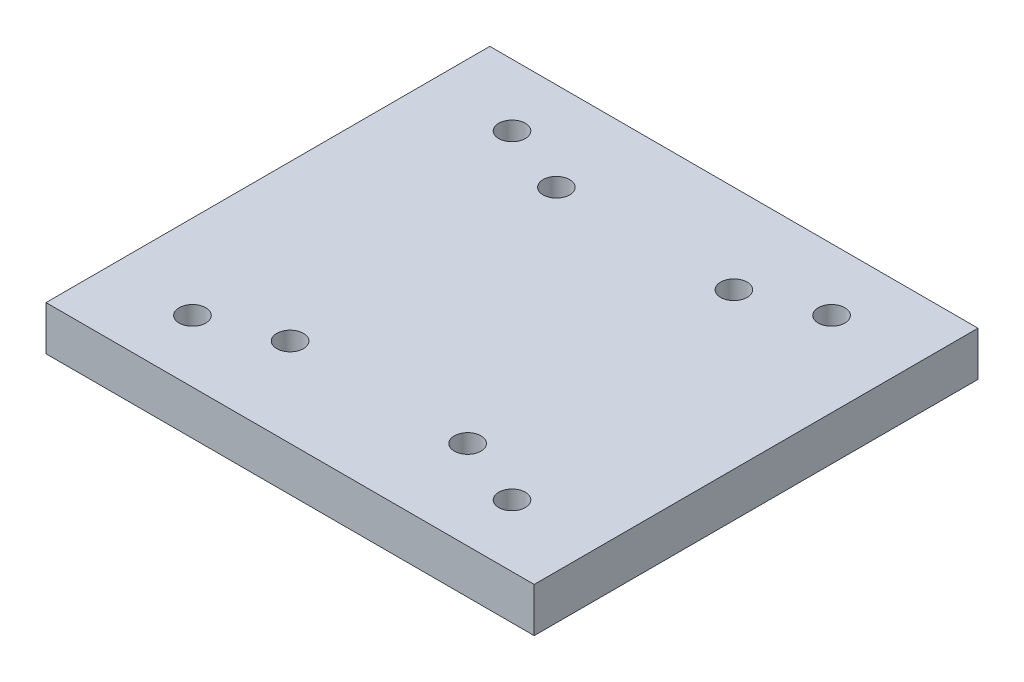
SolidWorks part; units mm, degrees
ref_plane "前视基准面" through (0, 0, 0) normal (0, 0, 1) x (1, 0, 0)
ref_plane "上视基准面" through (0, 0, 0) normal (0, 1, 0) x (1, 0, 0)
ref_plane "右视基准面" through (0, 0, 0) normal (1, 0, 0) x (0, 0, -1)
other "Configuration Table"
sketch "草图1" plane through (0, 0, 0) normal (0, 1, 0) x (1, 0, 0)
  line L1 (-27.5, 25) -> (27.5, 25)
  line L2 (-27.5, 25) -> (-27.5, -25)
  line L3 (-27.5, -25) -> (27.5, -25)
  line L4 (27.5, 25) -> (27.5, -25)
  line L5 (-27.5, 25) -> (27.5, -25) construction
  line L6 (-27.5, -25) -> (27.5, 25) construction
  point P0 (0, 0)
  dimension "D1" = 55
  dimension "D2" = 50
extrude "凸台-拉伸1" add sketch "草图1" along normal blind 5
sketch "草图2" plane through (0, 5, 0) normal (0, 1, 0) x (1, 0, 0)
  line L1 (-18, 18) -> (18, 18) construction
  line L2 (-18, 18) -> (-18, -18) construction
  line L3 (-18, -18) -> (18, -18) construction
  line L4 (18, 18) -> (18, -18) construction
  line L5 (-18, 18) -> (18, -18) construction
  line L6 (-18, -18) -> (18, 18) construction
  circle A0 centre (-18, 18) radius 1.5
  circle A1 centre (18, 18) radius 1.5
  circle A2 centre (18, -18) radius 1.5
  circle A3 centre (-18, -18) radius 1.5
  point P0 (0, 0)
  dimension "D3" = 3
  dimension "D1" = 36
  dimension "D2" = 36
extrude "切除-拉伸1" cut sketch "草图2" against normal through all
sketch "草图5" plane through (0, 5, 0) normal (0, 1, 0) x (1, 0, 0)
  line L1 (-10, 15) -> (10, 15) construction
  line L2 (-10, 15) -> (-10, -15) construction
  line L3 (-10, -15) -> (10, -15) construction
  line L4 (10, 15) -> (10, -15) construction
  line L5 (-10, 15) -> (10, -15) construction
  line L6 (-10, -15) -> (10, 15) construction
  circle A0 centre (-10, 15) radius 1.5
  circle A1 centre (10, 15) radius 1.5
  circle A2 centre (10, -15) radius 1.5
  circle A3 centre (-10, -15) radius 1.5
  point P0 (0, 0)
  dimension "D3" = 3
  dimension "D1" = 20
  dimension "D2" = 30
extrude "切除-拉伸2" cut sketch "草图5" against normal blind 10
sketch "草图3" plane through (0, 5, 0) normal (0, 1, 0) x (1, 0, 0)
  line L1 (-15.3442, 18) -> (-16.6721, 20.3)
  line L2 (-16.6721, 20.3) -> (-19.3279, 20.3)
  line L3 (-19.3279, 20.3) -> (-20.6558, 18)
  line L4 (-20.6558, 18) -> (-19.3279, 15.7)
  line L5 (-19.3279, 15.7) -> (-16.6721, 15.7)
  line L6 (-16.6721, 15.7) -> (-15.3442, 18)
  line L7 (20.6558, 18) -> (19.3279, 20.3)
  line L8 (19.3279, 20.3) -> (16.6721, 20.3)
  line L9 (16.6721, 20.3) -> (15.3442, 18)
  line L10 (15.3442, 18) -> (16.6721, 15.7)
  line L11 (16.6721, 15.7) -> (19.3279, 15.7)
  line L12 (19.3279, 15.7) -> (20.6558, 18)
  line L13 (20.6558, -18) -> (19.3279, -15.7)
  line L14 (19.3279, -15.7) -> (16.6721, -15.7)
  line L15 (16.6721, -15.7) -> (15.3442, -18)
  line L16 (15.3442, -18) -> (16.6721, -20.3)
  line L17 (16.6721, -20.3) -> (19.3279, -20.3)
  line L18 (19.3279, -20.3) -> (20.6558, -18)
  line L19 (-15.3442, -18) -> (-16.6721, -15.7)
  line L20 (-16.6721, -15.7) -> (-19.3279, -15.7)
  line L21 (-19.3279, -15.7) -> (-20.6558, -18)
  line L22 (-20.6558, -18) -> (-19.3279, -20.3)
  line L23 (-19.3279, -20.3) -> (-16.6721, -20.3)
  line L24 (-16.6721, -20.3) -> (-15.3442, -18)
  circle A0 centre (-18, 18) radius 2.3 construction
  circle A1 centre (18, 18) radius 2.3 construction
  circle A2 centre (18, -18) radius 2.3 construction
  circle A3 centre (-18, -18) radius 2.3 construction
  circle A4 centre (-18, 18) radius 1.5
  circle A5 centre (18, 18) radius 1.5
  circle A6 centre (18, -18) radius 1.5
  circle A7 centre (-18, -18) radius 1.5
  dimension "D1" = 3
  dimension "D2" = 4.6
sketch "草图4" plane through (0, 0, 0) normal (0, -1, 0) x (1, 0, 0)
  line L1 (-10, -15) -> (10, -15) construction
  line L2 (-10, -15) -> (-10, 15) construction
  line L3 (-10, 15) -> (10, 15) construction
  line L4 (10, -15) -> (10, 15) construction
  line L5 (-10, -15) -> (10, 15) construction
  line L6 (-10, 15) -> (10, -15) construction
  line L7 (-8.4123, -12.25) -> (-11.5877, -12.25)
  line L8 (-11.5877, -12.25) -> (-13.1754, -15)
  line L9 (-13.1754, -15) -> (-11.5877, -17.75)
  line L10 (-11.5877, -17.75) -> (-8.4123, -17.75)
  line L11 (-8.4123, -17.75) -> (-6.8246, -15)
  line L12 (-6.8246, -15) -> (-8.4123, -12.25)
  line L13 (11.5877, -12.25) -> (8.4123, -12.25)
  line L14 (8.4123, -12.25) -> (6.8246, -15)
  line L15 (6.8246, -15) -> (8.4123, -17.75)
  line L16 (8.4123, -17.75) -> (11.5877, -17.75)
  line L17 (11.5877, -17.75) -> (13.1754, -15)
  line L18 (13.1754, -15) -> (11.5877, -12.25)
  line L19 (11.5877, 12.25) -> (13.1754, 15)
  line L20 (13.1754, 15) -> (11.5877, 17.75)
  line L21 (11.5877, 17.75) -> (8.4123, 17.75)
  line L22 (8.4123, 17.75) -> (6.8246, 15)
  line L23 (6.8246, 15) -> (8.4123, 12.25)
  line L24 (8.4123, 12.25) -> (11.5877, 12.25)
  line L25 (-11.5877, 12.25) -> (-8.4123, 12.25)
  line L26 (-8.4123, 12.25) -> (-6.8246, 15)
  line L27 (-6.8246, 15) -> (-8.4123, 17.75)
  line L28 (-8.4123, 17.75) -> (-11.5877, 17.75)
  line L29 (-11.5877, 17.75) -> (-13.1754, 15)
  line L30 (-13.1754, 15) -> (-11.5877, 12.25)
  circle A0 centre (-10, -15) radius 1.5
  circle A1 centre (10, -15) radius 1.5
  circle A2 centre (10, 15) radius 1.5
  circle A3 centre (-10, 15) radius 1.5
  circle A4 centre (-10, -15) radius 2.75 construction
  circle A5 centre (10, -15) radius 2.75 construction
  circle A6 centre (10, 15) radius 2.75 construction
  circle A7 centre (-10, 15) radius 2.75 construction
  point P0 (0, 0)
  dimension "D3" = 3
  dimension "D4" = 5.5
  dimension "D1" = 30
  dimension "D2" = 20
